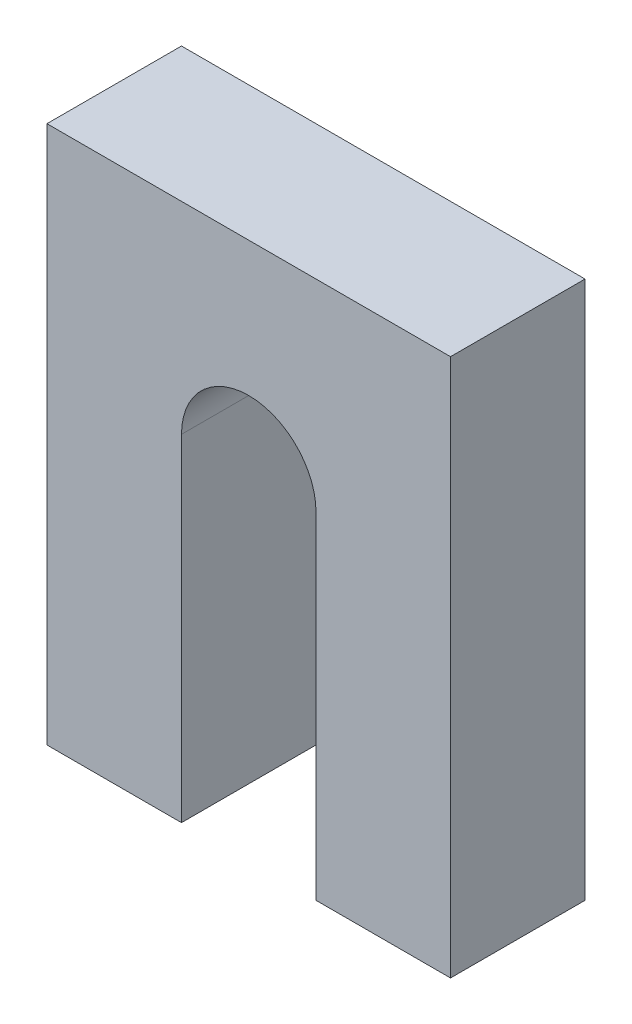
SolidWorks part; units mm, degrees
ref_plane "Front Plane" through (0, 0, 0) normal (0, 0, 1) x (1, 0, 0)
ref_plane "Top Plane" through (0, 0, 0) normal (0, 1, 0) x (1, 0, 0)
ref_plane "Right Plane" through (0, 0, 0) normal (1, 0, 0) x (0, 0, -1)
sketch "Sketch1" plane through (0, 0, 0) normal (0, 0, 1) x (1, 0, 0)
  line L0 (-5, 0) -> (-5, -25)
  line L1 (-5, -25) -> (-15, -25)
  line L2 (-15, -25) -> (-15, 15)
  line L3 (-15, 15) -> (15, 15)
  line L4 (0, 0) -> (0, 15) construction
  line L5 (15, -25) -> (15, 15)
  line L6 (5, -25) -> (15, -25)
  line L7 (5, 0) -> (5, -25)
  arc A0 (5, 0) -> (-5, 0) centre (0, 0) ccw
  dimension "D2" = 10
  dimension "D1" = 10
  dimension "D3" = 15
  dimension "D4" = 40
extrude "Boss-Extrude1" add sketch "Sketch1" along normal blind 10
